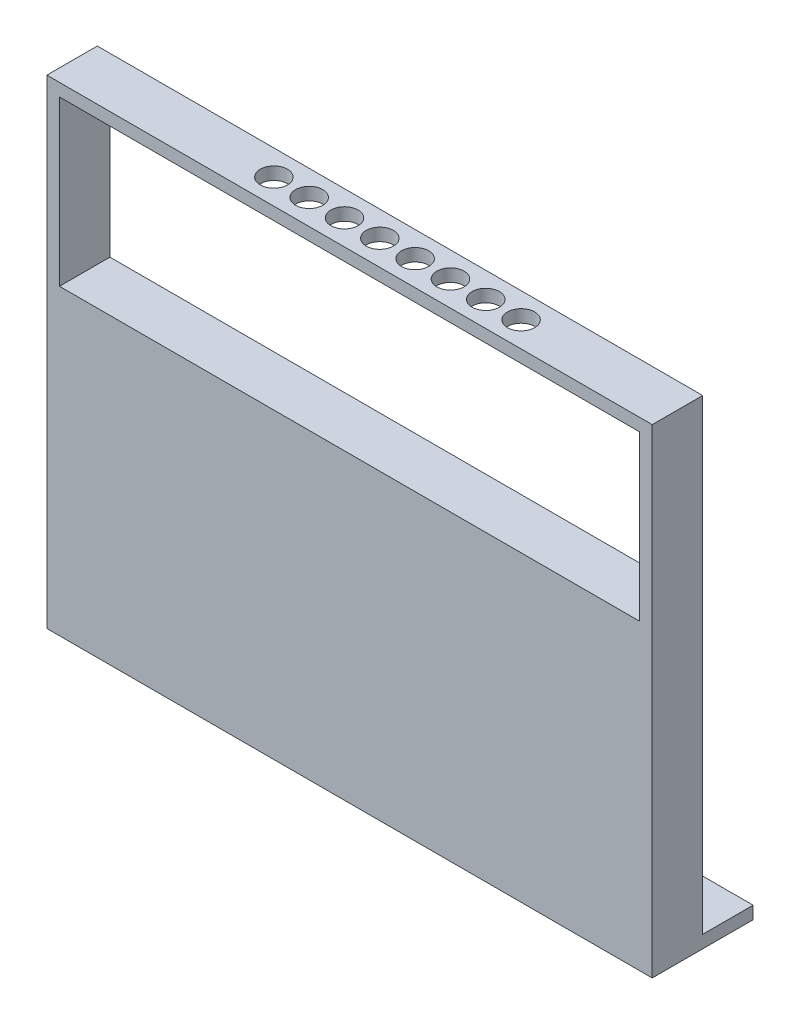
SolidWorks part; units mm, degrees
ref_plane "Front Plane" through (0, 0, 0) normal (0, 0, 1) x (1, 0, 0)
ref_plane "Top Plane" through (0, 0, 0) normal (0, 1, 0) x (1, 0, 0)
ref_plane "Right Plane" through (0, 0, 0) normal (1, 0, 0) x (0, 0, -1)
sketch "Sketch1" plane through (0, 0, 0) normal (0, 1, 0) x (1, 0, 0)
  line L1 (-76.2, -6.35) -> (76.2, -6.35)
  line L2 (-76.2, -6.35) -> (-76.2, 6.35)
  line L3 (-76.2, 6.35) -> (76.2, 6.35)
  line L4 (76.2, -6.35) -> (76.2, 6.35)
  line L5 (-76.2, -6.35) -> (76.2, 6.35) construction
  line L6 (-76.2, 6.35) -> (76.2, -6.35) construction
  point P0 (0, 0)
  dimension "D1" = 12.7
  dimension "D2" = 152.4
extrude "Boss-Extrude1" add sketch "Sketch1" along normal blind 76.2
sketch "Sketch2" plane through (0, 0, 0) normal (0, 1, 0) x (1, 0, 0)
  line L0 (-76.2, 6.35) -> (-76.2, -6.35) construction
  line L1 (-76.2, 12.7) -> (-76.2, 6.35)
  line L2 (-76.2, 6.35) -> (76.2, 6.35)
  line L3 (76.2, 19.05) -> (-76.2, 19.05)
  line L4 (-76.2, 12.7) -> (-76.2, 19.05)
  line L5 (0, 0) -> (-76.2, 19.05) construction
  line L6 (76.2, 19.05) -> (0, 0) construction
  line L7 (76.2, 6.35) -> (-76.2, 6.35) construction
  line L8 (-23.5905, 19.05) -> (-23.5905, 6.35) construction
  line L9 (-23.5905, 12.7) -> (-76.2, 12.7) construction
  line L10 (76.2, 6.35) -> (76.2, 19.05)
  circle A0 centre (-69.85, 12.7) radius 3.175
  circle A1 centre (-44.45, 12.7) radius 3.175
  circle A2 centre (-19.05, 12.7) radius 3.175
  circle A3 centre (6.35, 12.7) radius 3.175
  circle A4 centre (31.75, 12.7) radius 3.175
  circle A5 centre (57.15, 12.7) radius 3.175
  point P0 (0, 0)
  dimension "D2" = 6.35
  dimension "D1" = 12.7
  dimension "D3" = 6
  dimension "D4" = 6.35
extrude "Boss-Extrude4" add sketch "Sketch2" along normal blind 3.175
sketch "Sketch3" plane through (0, 0, 6.35) normal (0, 0, 1) x (1, 0, 0)
  line L0 (-76.2, 76.2) -> (-76.2, 120.65)
  line L1 (-76.2, 120.65) -> (76.2, 120.65)
  line L2 (76.2, 120.65) -> (76.2, 76.2)
  line L3 (76.2, 76.2) -> (76.2, 0) construction
  line L4 (-76.2, 76.2) -> (-76.2, 0) construction
  line L5 (76.2, 76.2) -> (73.025, 76.2)
  line L6 (-76.2, 76.2) -> (76.2, 76.2) construction
  line L7 (73.025, 76.2) -> (73.025, 117.475)
  line L8 (73.025, 117.475) -> (-73.025, 117.475)
  line L9 (-73.025, 117.475) -> (-73.025, 76.2)
  line L10 (-73.025, 76.2) -> (-76.2, 76.2)
  line L11 (-73.025, 117.475) -> (-73.025, 120.65) construction
  dimension "D1" = 3.175
  dimension "D2" = 44.45
extrude "Boss-Extrude5" add sketch "Sketch3" against normal up to surface (12.7 mm away) up to face at (0, 39.6875, -6.35)
sketch "Sketch4" plane through (0, 120.65, 0) normal (0, 1, 0) x (1, 0, 0)
  line L0 (-76.2, 6.35) -> (-76.2, -6.35) construction
  circle A0 centre (-25.4, 0) radius 3.429
  circle A1 centre (-16.51, 0) radius 3.429
  circle A2 centre (-7.62, 0) radius 3.429
  circle A3 centre (1.27, 0) radius 3.429
  circle A4 centre (10.16, 0) radius 3.429
  circle A5 centre (19.05, 0) radius 3.429
  circle A6 centre (27.94, 0) radius 3.429
  circle A7 centre (36.83, 0) radius 3.429
  dimension "D1" = 6.858
  dimension "D2" = 50.8
  dimension "D4" = 8.89
  dimension "D3" = 8
extrude "Cut-Extrude1" cut sketch "Sketch4" against normal up to next
